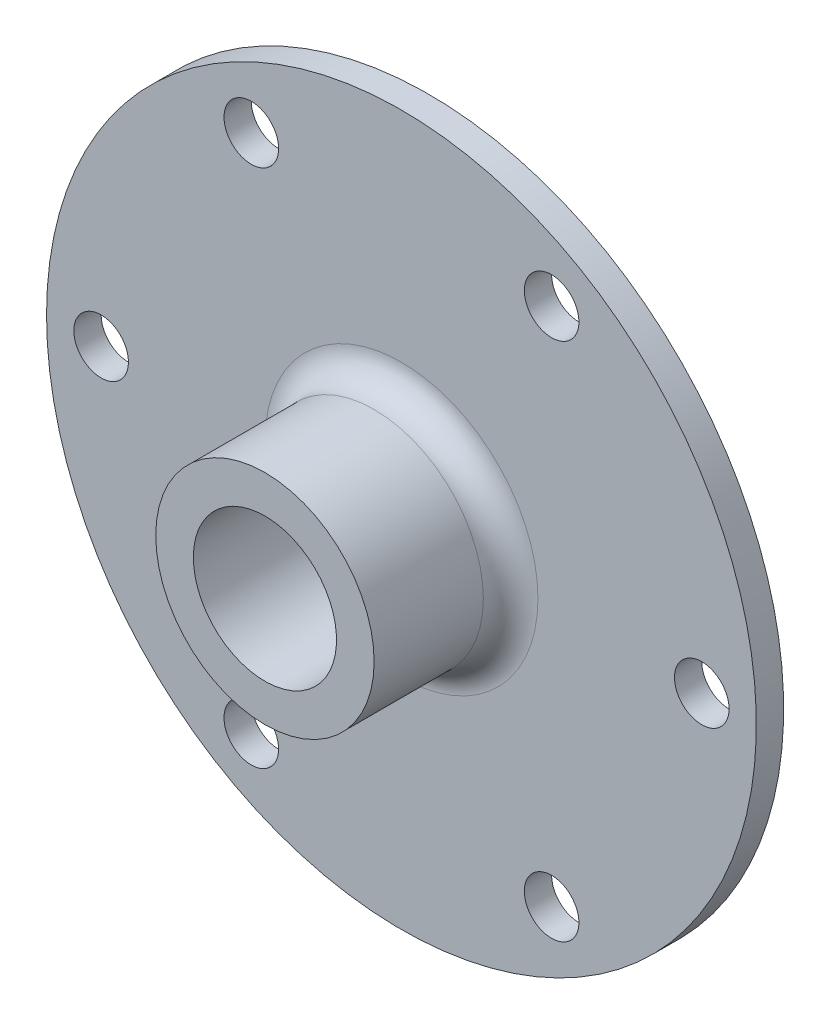
SolidWorks part; units mm, degrees
material "AISI 1020"
ref_plane "Front Plane" through (0, 0, 0) normal (0, 0, 1) x (1, 0, 0)
ref_plane "Top Plane" through (0, 0, 0) normal (0, 1, 0) x (1, 0, 0)
ref_plane "Right Plane" through (0, 0, 0) normal (1, 0, 0) x (0, 0, -1)
sketch "Sketch1" plane through (0, 0, 0) normal (1, 0, 0) x (0, 0, -1)
  line L2 (0, 0) -> (0, 41.275)
  line L3 (0, 41.275) -> (-3.175, 41.275)
  line L4 (-3.175, 12.7) -> (-3.175, 41.275)
  line L5 (0, 0) -> (-19.05, 0)
  line L7 (-3.175, 12.7) -> (-19.05, 12.7)
  line L8 (-19.05, 0) -> (-19.05, 12.7)
  dimension "D1" = 19.05
  dimension "D2" = 41.275
  dimension "D3" = 3.175
  dimension "D4" = 12.7
revolve "Revolve1" add sketch "Sketch1" angle 360 about L5
sketch "Sketch2" plane through (0, 0, 0) normal (0, 0, 1) x (1, 0, 0)
  circle A0 centre (0, 0) radius 8.3248
  dimension "D1" = 16.6495
extrude "Cut-Extrude5" cut sketch "Sketch2" along normal through all
sketch "Sketch3" plane through (0, 0, 3.175) normal (0, 0, 1) x (1, 0, 0)
  line L0 (0, 0) -> (34.925, 0) construction
  circle A0 centre (34.925, 0) radius 3.175
  dimension "D2" = 6.35
  dimension "D1" = 34.925
extrude "Cut-Extrude6" cut sketch "Sketch3" against normal through all
pattern_circular "CirPattern2" count 6 over 360 about axis through (0, 0, 0) along (0, 0, 1) of "Cut-Extrude6"
fillet "Fillet1" radius 3.175 1 edges at (-12.7, 0, 3.175)
